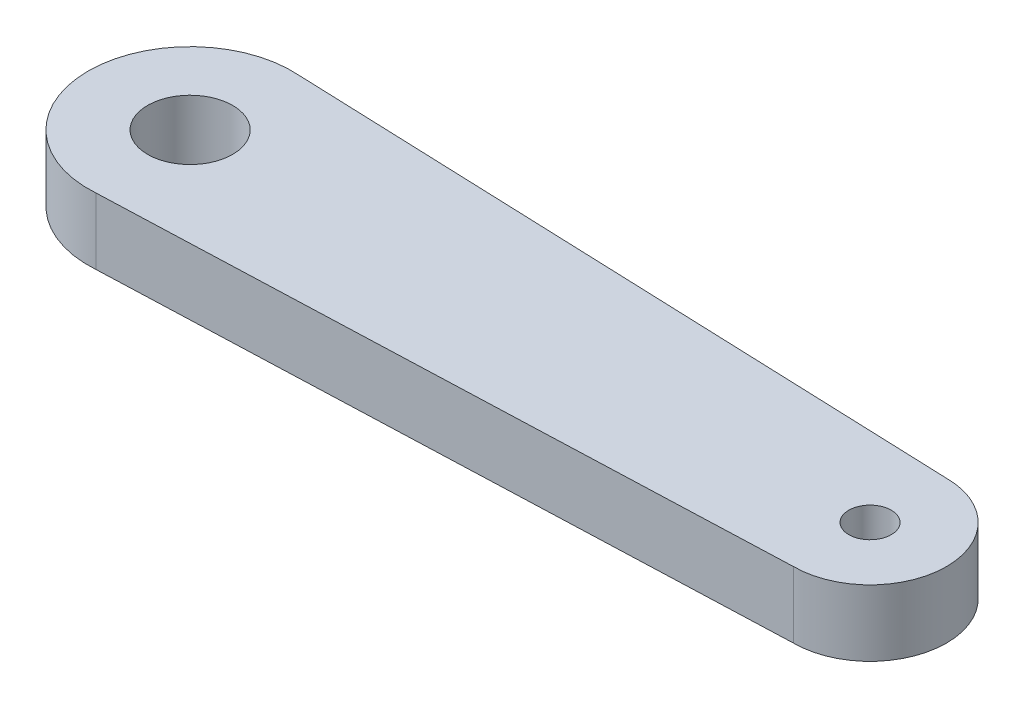
SolidWorks part; units mm, degrees
ref_plane "Front Plane" through (0, 0, 0) normal (0, 0, 1) x (1, 0, 0)
ref_plane "Top Plane" through (0, 0, 0) normal (0, 1, 0) x (1, 0, 0)
ref_plane "Right Plane" through (0, 0, 0) normal (1, 0, 0) x (0, 0, -1)
sketch "Sketch1" plane through (0, 0, 0) normal (0, 1, 0) x (1, 0, 0)
  line L0 (0.4494, 5.9831) -> (40, 4.5)
  line L1 (0.4494, -5.9831) -> (40, -4.5)
  arc A0 (0.4494, 5.9831) -> (0.4494, -5.9831) centre (0, 0) ccw
  arc A1 (40, -4.5) -> (40, 4.5) centre (40, 0) ccw
  dimension "D2" = 6
  dimension "D3" = 4.5
  dimension "D1" = 40
extrude "Boss-Extrude1" add sketch "Sketch1" along normal blind 3.9 contours L1 A1 L0 A0
sketch "Sketch2" plane through (0, 3.9, 0) normal (0, 1, 0) x (1, 0, 0)
  circle A0 centre (0, 0) radius 2.5
  circle A1 centre (40, 0) radius 1.25
  dimension "D1" = 5
  dimension "D2" = 2.5
extrude "Cut-Extrude1" cut sketch "Sketch2" against normal blind 10.5 and the other way blind 16
